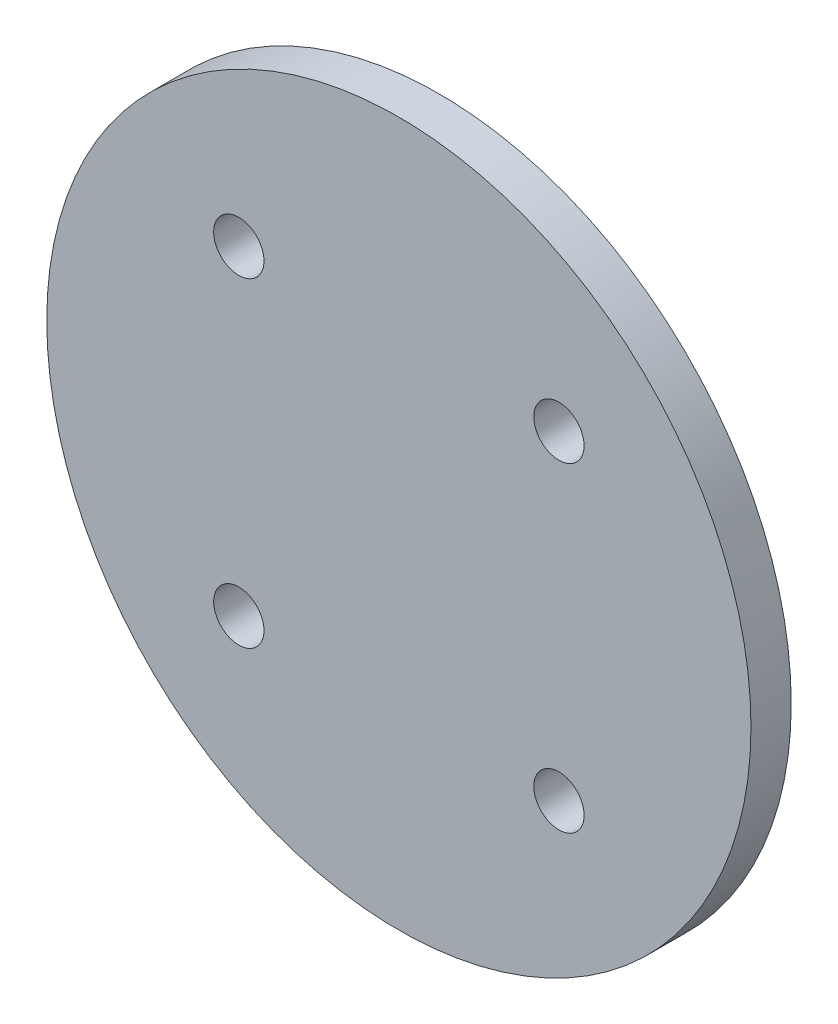
SolidWorks part; units mm, degrees
ref_plane "Front Plane" through (0, 0, 0) normal (0, 0, 1) x (1, 0, 0)
ref_plane "Top Plane" through (0, 0, 0) normal (0, 1, 0) x (1, 0, 0)
ref_plane "Right Plane" through (0, 0, 0) normal (1, 0, 0) x (0, 0, -1)
sketch "Sketch1" plane through (0, 0, 0) normal (0, 0, 1) x (1, 0, 0)
  line L0 (-15.9099, -15.9099) -> (15.9099, 15.9099) construction
  line L1 (15.9099, 15.9099) -> (-15.9099, 15.9099) construction
  line L2 (-15.9099, 15.9099) -> (15.9099, -15.9099) construction
  line L3 (15.9099, -15.9099) -> (-15.9099, -15.9099) construction
  line L4 (-15.9099, -15.9099) -> (-15.9099, 15.9099) construction
  line L5 (15.9099, 15.9099) -> (15.9099, -15.9099) construction
  circle A1 centre (15.9099, 15.9099) radius 2.5
  circle A2 centre (15.9099, -15.9099) radius 2.5
  circle A3 centre (-15.9099, -15.9099) radius 2.5
  circle A4 centre (-15.9099, 15.9099) radius 2.5
  circle A5 centre (0, 0) radius 35
  point P14 (0, 0)
  dimension "D1" = 4
extrude "Boss-Extrude1" add sketch "Sketch1" along normal blind 4 contours A4 | A1 | A2 | A3 | A5
